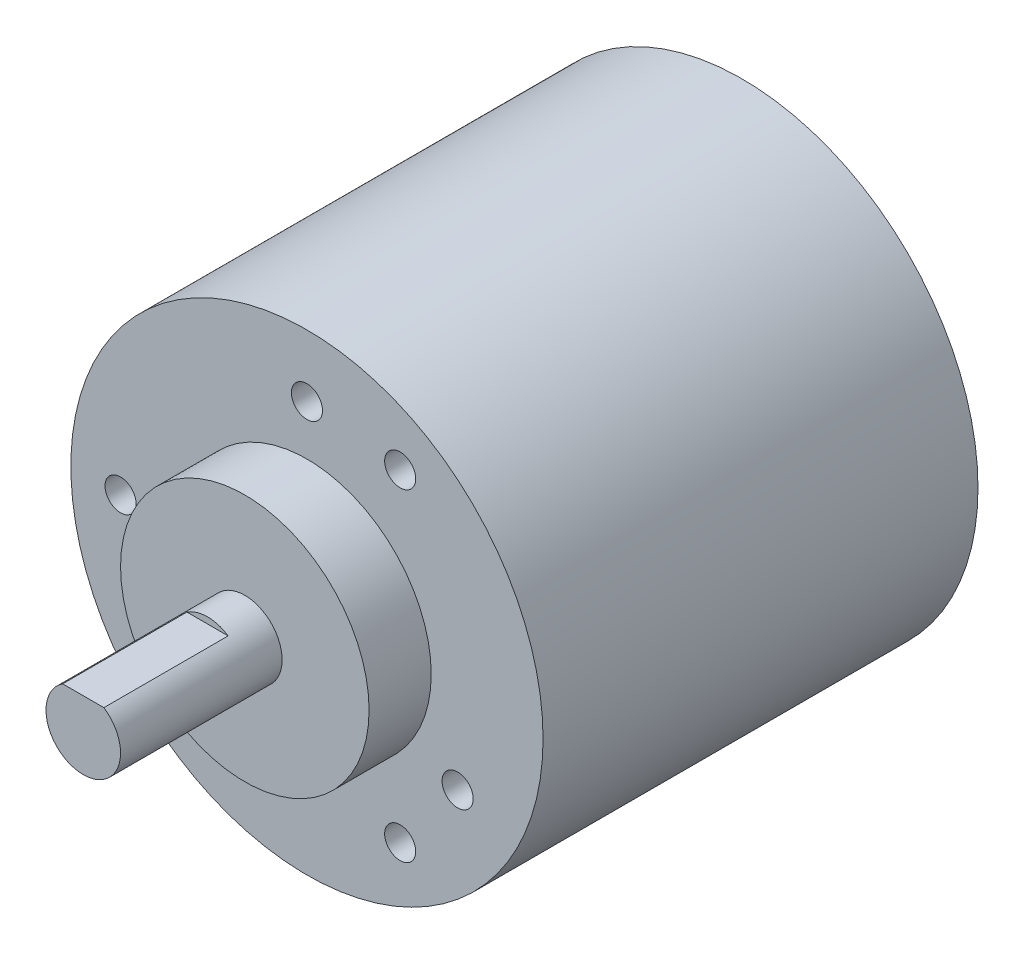
SolidWorks part; units mm, degrees
ref_plane "Front Plane" through (0, 0, 0) normal (0, 0, 1) x (1, 0, 0)
ref_plane "Top Plane" through (0, 0, 0) normal (0, 1, 0) x (1, 0, 0)
ref_plane "Right Plane" through (0, 0, 0) normal (1, 0, 0) x (0, 0, -1)
sketch "Sketch1" plane through (0, 0, 0) normal (0, 0, 1) x (1, 0, 0)
  circle A0 centre (0, 0) radius 19
  dimension "D1" = 38
extrude "Boss-Extrude1" add sketch "Sketch1" along normal blind 35
sketch "Sketch2" plane through (0, 0, 0) normal (0, 0, 1) x (1, 0, 0)
  circle A0 centre (0, 0) radius 10
  dimension "D1" = 20
extrude "Boss-Extrude2" add sketch "Sketch2" along normal blind 5 from surface at 35 starting at face at (19, 0, 35)
sketch "Sketch3" plane through (0, 0, 0) normal (0, 0, 1) x (1, 0, 0)
  circle A0 centre (0, 0) radius 3
  dimension "D1" = 6
extrude "Boss-Extrude3" add sketch "Sketch3" along normal blind 13 from surface at 40 starting at face at (10, 0, 40)
sketch "Sketch4" plane through (0, 0, 53) normal (0, 0, 1) x (1, 0, 0)
  line L0 (-1.6583, 2.5) -> (1.6583, 2.5)
  circle A1 centre (0, 0) radius 3
  arc A2 (1.6583, 2.5) -> (-1.6583, 2.5) centre (0, 0) ccw
  dimension "D2" = 2.5
  dimension "D1" = 0
extrude "Cut-Extrude1" cut sketch "Sketch4" against normal blind 10
hole_wizard "M3x0.5 Tapped Hole1" positions "Sketch6" profile "Sketch7" tap size "M3x0.5" standard "ANSI Metric"
sketch "Sketch6" plane through (0, 0, 35) normal (0, 0, 1) x (1, 0, 0)
  line L0 (0, 14) -> (0, 0) construction
  line L1 (0, 0) -> (7.5, 12.9904) construction
  circle A0 centre (0, 0) radius 14 construction
  circle A1 centre (0, 0) radius 15 construction
  point P0 (0, 14)
  point P2 (7.5, 12.9904)
  point P21 (12.1244, -7)
  point P22 (7.5, -12.9904)
  point P23 (-12.1244, -7)
  point P24 (-15, 0)
  point P25 (0, 0)
  point P26 (0, 0)
  point P27 (1.5998, 14)
  dimension "D1" = 28
  dimension "D2" = 30
  dimension "D3" = 30
  dimension "D4" = 3
sketch "Sketch7" plane through (0, 14, 35) normal (1, 0, 0) x (0, -1, 0)
  line L0 (0, 0) -> (0, 8.2511)
  line L1 (0, 8.2511) -> (1.25, 7.5)
  line L2 (1.25, 7.5) -> (1.25, 0)
  line L5 (1.25, 0) -> (0, 0)
  line L10 (0, 8.2511) -> (-1.25, 7.5) construction
  line L11 (0, -6.35) -> (0, 107.95) construction
  dimension "Tap Drill Dia." = 2.5
  dimension "Tap Drill Depth" = 7.5
  dimension "Drill Angle" = 118
cosmetic thread "Hole Thread1"
cosmetic thread "Hole Thread2"
cosmetic thread "Hole Thread3"
cosmetic thread "Hole Thread4"
cosmetic thread "Hole Thread5"
cosmetic thread "Hole Thread6"
